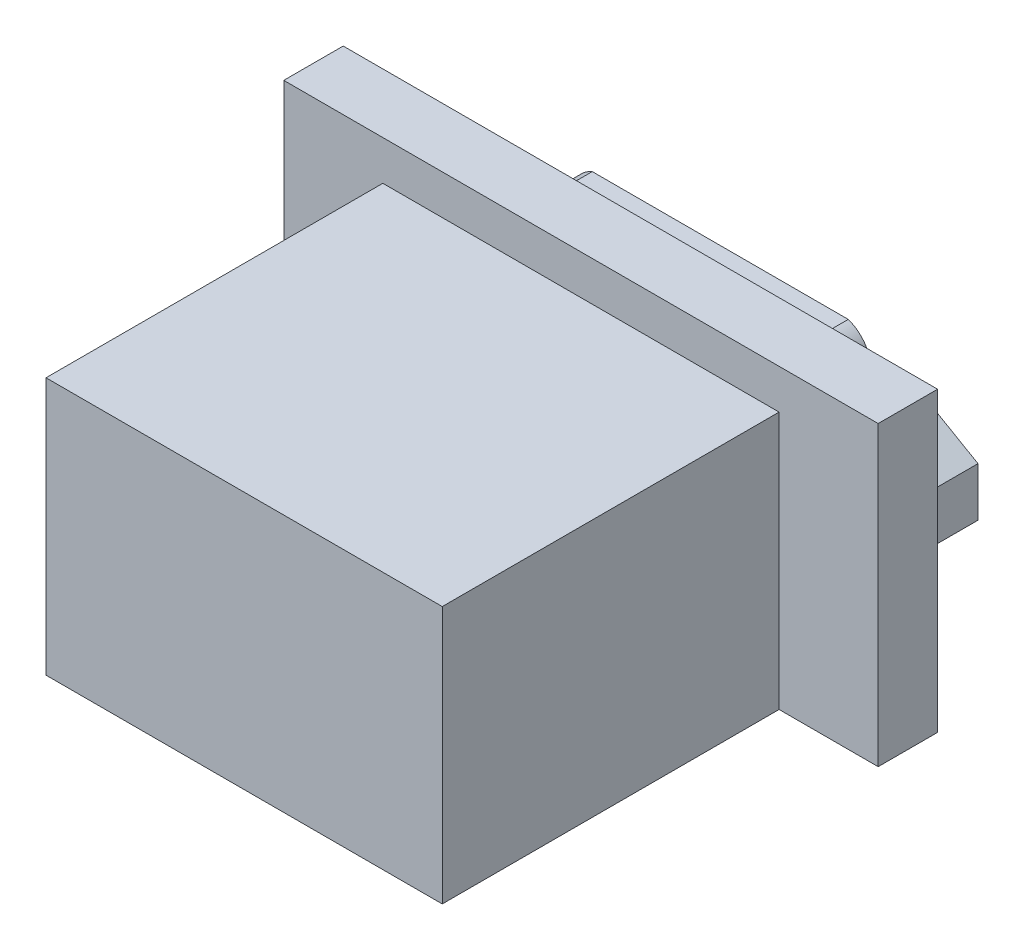
SolidWorks part; units mm, degrees
ref_plane "Front Plane" through (0, 0, 0) normal (0, 0, 1) x (1, 0, 0)
ref_plane "Top Plane" through (0, 0, 0) normal (0, 1, 0) x (1, 0, 0)
ref_plane "Right Plane" through (0, 0, 0) normal (1, 0, 0) x (0, 0, -1)
sketch "Sketch1" plane through (0, 0, 0) normal (0, 1, 0) x (1, 0, 0)
  line L1 (0, 0) -> (30, 0)
  line L2 (0, 0) -> (0, 20)
  line L3 (0, 20) -> (30, 20)
  line L4 (30, 0) -> (30, 20)
  dimension "D1" = 30
  dimension "D2" = 20
extrude "Boss-Extrude1" add sketch "Sketch1" along normal blind 15
sketch "Sketch2" plane through (0, 0, 0) normal (0, 0, 1) x (1, 0, 0)
  line L0 (30, 15) -> (30, 0) construction
  line L1 (30, 15) -> (25, 15)
  line L2 (30, 15) -> (30, 0)
  line L3 (30, 0) -> (25, 0)
  line L4 (25, 15) -> (25, 0)
  line L5 (5, 15) -> (0, 15)
  line L6 (5, 15) -> (5, 0)
  line L7 (5, 0) -> (0, 0)
  line L8 (0, 15) -> (0, 0)
  line L9 (0, 15) -> (30, 15) construction
  line L10 (0, 0) -> (30, 0) construction
  point P8 (0, 15)
  point P10 (0, 0)
  point P12 (30, 15)
  point P17 (30, 0)
  dimension "D1" = 5
  dimension "D2" = 5
extrude "Cut-Extrude4" cut sketch "Sketch2" against normal blind 17
sketch "Sketch3" plane through (0, 0, 0) normal (0, 0, 1) x (1, 0, 0)
  line L0 (25, 15) -> (25, 0) construction
  line L1 (25, 15) -> (5, 15)
  line L2 (25, 15) -> (25, 13)
  line L3 (25, 13) -> (5, 13)
  line L4 (5, 15) -> (5, 13)
  point P4 (5, 15)
  point P6 (25, 13)
  dimension "D1" = 2
extrude "Cut-Extrude5" cut sketch "Sketch3" against normal blind 17
sketch "Sketch4" plane through (0, 0, -20) normal (0, 0, -1) x (-1, 0, 0)
  line L0 (-21.4902, 11.7966) -> (-8.5695, 11.7966)
  line L1 (-20.0697, 2.7966) -> (-10.8431, 2.7966)
  line L4 (-7.5311, 10.2738) -> (-9.8884, 3.5151)
  line L5 (-22.5997, 9.8605) -> (-21.3155, 3.6501)
  line L6 (-30, 15) -> (-30, 0) construction
  line L7 (0, 15) -> (0, 0) construction
  line L8 (-30, 15) -> (0, 15) construction
  line L9 (-30, 0) -> (0, 0) construction
  arc A0 (-21.4902, 11.7966) -> (-22.5997, 9.8605) centre (-20.9321, 10.1908) ccw
  arc A1 (-7.5311, 10.2738) -> (-8.5695, 11.7966) centre (-9.2306, 10.2304) ccw
  arc A2 (-9.8884, 3.5151) -> (-10.8431, 2.7966) centre (-11.1099, 4.1446) cw
  arc A3 (-20.017, 2.7966) -> (-21.3155, 3.6501) centre (-20.0434, 4.171) cw
  dimension "D6" = 1.7
  dimension "D7" = 1.7
  dimension "D8" = 1.3746
  dimension "D9" = 1.3741
  dimension "D1" = 6.2104
  dimension "D2" = 11.683
  dimension "D3" = 9
  dimension "D4" = 160.772
  dimension "D5" = 3.2034
  dimension "D10" = 2.7966
  dimension "D11" = 1.3513
  dimension "D12" = 1.3607
sketch "Sketch6" plane through (0, 0, -20) normal (0, 0, -1) x (-1, 0, 0)
  line L0 (-8.5695, 11.7966) -> (-21.4902, 11.7966)
  line L1 (-10.8431, 2.7966) -> (-20.0697, 2.7966)
  line L2 (-22.5997, 9.8605) -> (-21.3155, 3.6501)
  line L3 (-7.5311, 10.2738) -> (-9.8884, 3.5151)
  arc A0 (-20.0697, 2.7966) -> (-21.3155, 3.6501) centre (-20.0601, 4.1465) cw
  arc A1 (-10.8431, 2.7966) -> (-9.8884, 3.5151) centre (-11.0937, 4.1231) ccw
  arc A2 (-8.5695, 11.7966) -> (-7.5311, 10.2738) centre (-9.2306, 10.2304) cw
  arc A3 (-21.4902, 11.7966) -> (-22.5997, 9.8605) centre (-20.9321, 10.1908) ccw
  dimension "D1" = 1.7
  dimension "D2" = 1.7
  dimension "D3" = 1.35
  dimension "D4" = 1.35
extrude "Boss-Extrude3" add sketch "Sketch6" along normal blind 4
sketch "Sketch7" plane through (0, 0, -20) normal (0, 0, -1) x (-1, 0, 0)
  line L1 (-3.9859, 10.0032) -> (-6.1283, 8.7663)
  line L2 (-6.1283, 8.7663) -> (-6.1283, 6.2926)
  line L3 (-6.1283, 6.2926) -> (-3.9859, 5.0557)
  line L4 (-3.9859, 5.0557) -> (-1.8436, 6.2926)
  line L5 (-1.8436, 6.2926) -> (-1.8436, 8.7663)
  line L6 (-1.8436, 8.7663) -> (-3.9859, 10.0032)
  line L7 (-25.8963, 10.0032) -> (-28.0386, 8.7663)
  line L8 (-28.0386, 8.7663) -> (-28.0386, 6.2926)
  line L9 (-28.0386, 6.2926) -> (-25.8963, 5.0557)
  line L10 (-25.8963, 5.0557) -> (-23.7539, 6.2926)
  line L11 (-23.7539, 6.2926) -> (-23.7539, 8.7663)
  line L12 (-23.7539, 8.7663) -> (-25.8963, 10.0032)
  circle A0 centre (-3.9859, 7.5294) radius 2.1423 construction
  circle A1 centre (-25.8963, 7.5294) radius 2.1423 construction
  dimension "D1" = 2.4737
  dimension "D2" = 2.4737
extrude "Boss-Extrude4" add sketch "Sketch7" along normal blind 4
sketch "Sketch8" plane through (0, 0, -24) normal (0, 0, -1) x (-1, 0, 0)
  circle A0 centre (-25.9498, 7.4801) radius 1.5792
  circle A1 centre (-4.0104, 7.4801) radius 1.58
  point P4 (-3.6919, 7.4801)
  point P5 (-4.0104, 7.4801)
  dimension "D1" = 3.1584
  dimension "D2" = 3.16
extrude "Cut-Extrude8" cut sketch "Sketch8" against normal blind 4
sketch "Sketch9" plane through (0, 0, -24) normal (0, 0, -1) x (-1, 0, 0)
  line L0 (-8.7487, 10.5062) -> (-21.3314, 10.485)
  line L1 (-11.0183, 3.4271) -> (-20.0434, 3.4119)
  line L2 (-8.7487, 10.5062) -> (-11.0183, 3.4271)
  line L3 (-21.3314, 10.485) -> (-20.0434, 3.4119)
  dimension "D1" = 7.0753
extrude "Cut-Extrude12" cut sketch "Sketch9" against normal blind 4
sketch "Sketch10" plane through (0, 0, -20) normal (0, 0, -1) x (-1, 0, 0)
  circle A0 centre (-10.6997, 9.1126) radius 0.75
  circle A1 centre (-11.8146, 6.843) radius 0.75
  circle A2 centre (-12.6997, 9.1126) radius 0.75
  circle A3 centre (-13.8146, 6.843) radius 0.75
  circle A4 centre (-14.6997, 9.1126) radius 0.75
  circle A5 centre (-15.8146, 6.843) radius 0.75
  circle A6 centre (-16.6997, 9.1126) radius 0.75
  circle A7 centre (-17.8146, 6.843) radius 0.75
  circle A8 centre (-18.6997, 9.1126) radius 0.75
  circle A9 centre (-19.8146, 6.843) radius 0.75
  dimension "D1" = 1.5
  dimension "D2" = 1.5
extrude "Boss-Extrude5" add sketch "Sketch10" along normal blind 3
